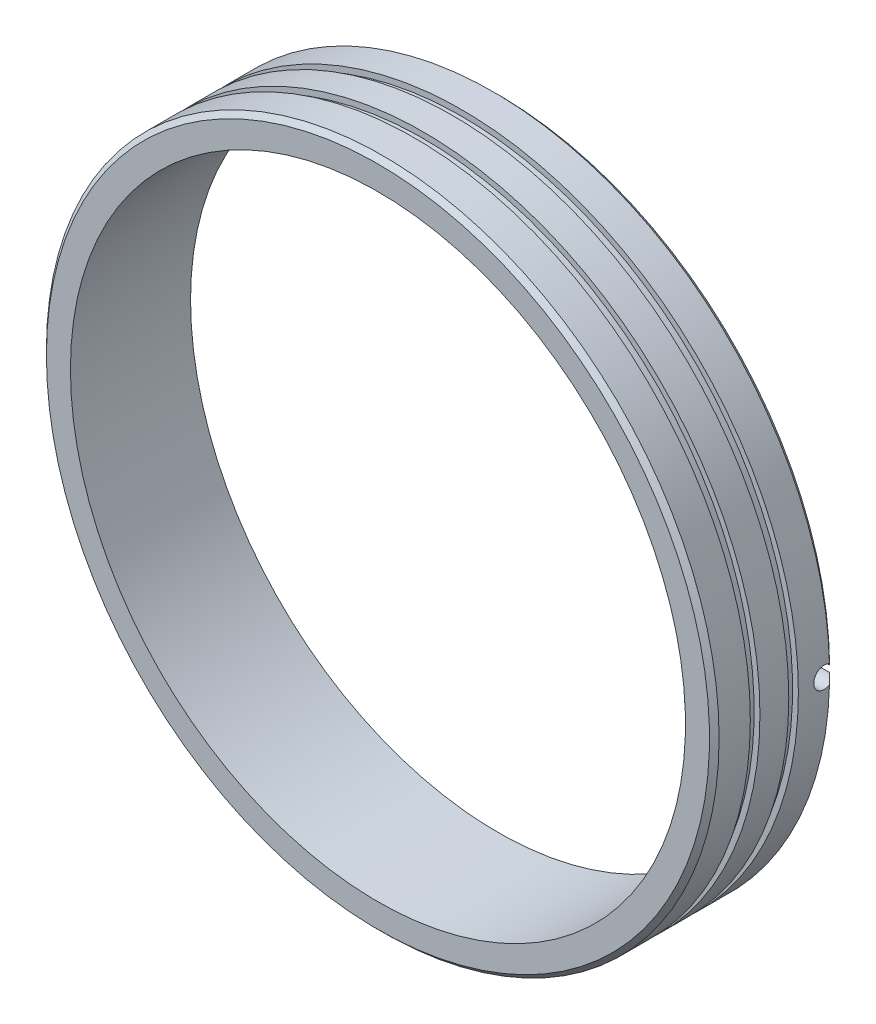
SolidWorks part; units mm, degrees
ref_plane "Front Plane" through (0, 0, 0) normal (0, 0, 1) x (1, 0, 0)
ref_plane "Top Plane" through (0, 0, 0) normal (0, 1, 0) x (1, 0, 0)
ref_plane "Right Plane" through (0, 0, 0) normal (1, 0, 0) x (0, 0, -1)
sketch "Sketch1" plane through (0, 0, 0) normal (1, 0, 0) x (0, 0, -1)
  line L0 (-1.5, 64) -> (-26.5, 64)
  line L1 (-26.5, 64) -> (-26.5, 69)
  line L2 (-26.5, 69) -> (-25.5, 70)
  line L3 (-25.5, 70) -> (-19, 70)
  line L4 (-19, 70) -> (-19, 68.8)
  line L5 (-19, 68.8) -> (-17, 68.8)
  line L6 (-17, 68.8) -> (-17, 70)
  line L7 (-17, 70) -> (-11, 70)
  line L8 (-11, 70) -> (-11, 68.8)
  line L9 (-11, 68.8) -> (-9, 68.8)
  line L10 (-9, 68.8) -> (-9, 70)
  line L11 (-9, 70) -> (-2.5, 70)
  line L12 (-2.5, 70) -> (-1.5, 69)
  line L13 (-1.5, 69) -> (-1.5, 64)
  line L14 (0, 0) -> (-30, 0) construction
revolve "Tyre" add sketch "Sketch1" angle 360 about L14
ref_plane "P_Right_63" through (63, 0, 0) normal (1, 0, 0) x (0, 0, -1)
sketch "Sketch2" plane through (63, 0, 0) normal (1, 0, 0) x (0, 0, -1)
  circle A0 centre (-3.6, 0) radius 2.2
extrude "Grub_key_hole" cut sketch "Sketch2" along normal blind 8
